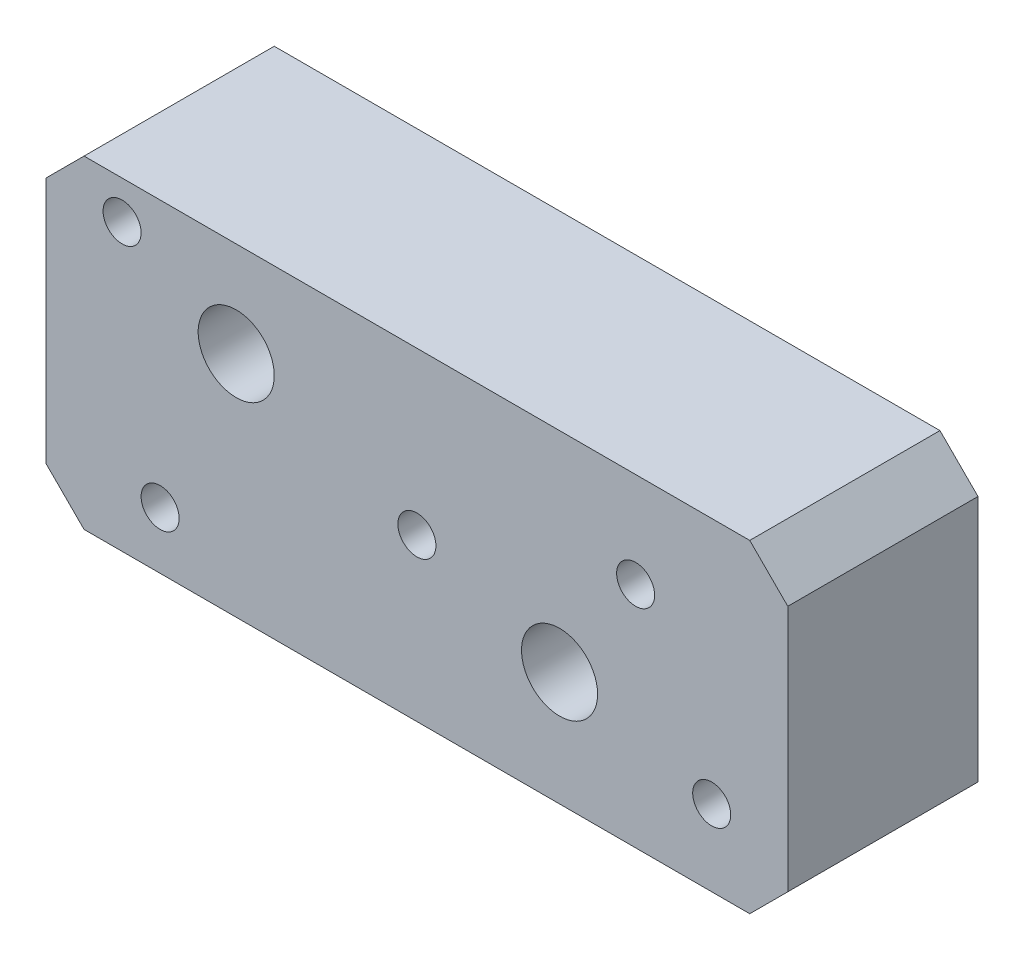
SolidWorks part; units mm, degrees
ref_plane "Front Plane" through (0, 0, 0) normal (0, 0, 1) x (1, 0, 0)
ref_plane "Top Plane" through (0, 0, 0) normal (0, 1, 0) x (1, 0, 0)
ref_plane "Right Plane" through (0, 0, 0) normal (1, 0, 0) x (0, 0, -1)
sketch "Sketch2" plane through (0, 0, 0) normal (0, 0, 1) x (1, 0, 0)
  line L0 (-17.5, 8.5) -> (-19.5, 6.5)
  line L1 (17.5, -8.5) -> (-17.5, -8.5)
  line L2 (19.5, -6.5) -> (19.5, 6.5)
  line L3 (17.5, 8.5) -> (-17.5, 8.5)
  line L4 (-19.5, -6.5) -> (-19.5, 6.5)
  line L5 (19.5, -8.5) -> (-19.5, 8.5) construction
  line L6 (19.5, 8.5) -> (-19.5, -8.5) construction
  line L7 (-17.5, -8.5) -> (-19.5, -6.5)
  line L8 (19.5, -6.5) -> (17.5, -8.5)
  line L9 (19.5, 6.5) -> (17.5, 8.5)
  circle A0 centre (0, 0) radius 1
  circle A1 centre (-13.5, -5.5) radius 1
  circle A2 centre (-15.5, 6.5) radius 1
  circle A3 centre (-9.5, 3.5) radius 2
  circle A4 centre (7.5, -2.5) radius 2
  circle A5 centre (15.5, -4.5) radius 1
  circle A6 centre (11.5, 3.5) radius 1
  dimension "D1" = 2
  dimension "D12" = 2
  dimension "D13" = 6
  dimension "D14" = 3
  dimension "D15" = 4
  dimension "D16" = 15
  dimension "D17" = 4
  dimension "D18" = 12
  dimension "D19" = 10
  dimension "D20" = 12
  dimension "D21" = 6
  dimension "D22" = 4
  dimension "D23" = 4
  dimension "D24" = 8
  dimension "D25" = 12
  dimension "D2" = 2
  dimension "D3" = 45
  dimension "D4" = 2
  dimension "D5" = 45
  dimension "D6" = 2
  dimension "D7" = 45
  dimension "D8" = 2
  dimension "D9" = 45
  dimension "D10" = 39
  dimension "D11" = 17
extrude "Boss-Extrude1" add sketch "Sketch2" along normal mid plane 10
